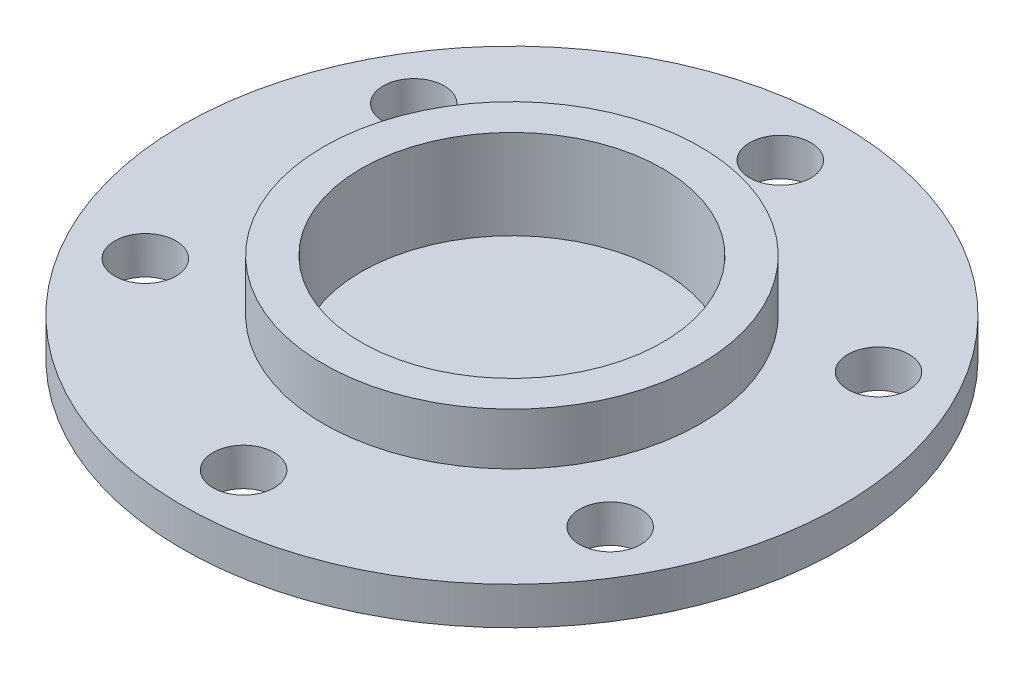
SolidWorks part; units mm, degrees
ref_plane "Front Plane" through (0, 0, 0) normal (0, 0, 1) x (1, 0, 0)
ref_plane "Top Plane" through (0, 0, 0) normal (0, 1, 0) x (1, 0, 0)
ref_plane "Right Plane" through (0, 0, 0) normal (1, 0, 0) x (0, 0, -1)
sketch "Sketch1" plane through (0, 0, 0) normal (0, 0, 1) x (1, 0, 0)
  line L0 (0, -4) -> (0, -14.5)
  line L1 (0, 0) -> (0, -26.9976) construction
  line L3 (-20.064, -4) -> (-35, -4)
  line L4 (-35, -4) -> (-35, 0)
  line L5 (-35, 0) -> (-20, 0)
  line L6 (-20, 0) -> (-20, 5.5)
  line L7 (-20, 5.5) -> (-16, 5.5)
  line L8 (-16, 5.5) -> (-16, -4)
  line L9 (-16, -4) -> (0, -4)
  line L10 (-20.064, -4) -> (0, -14.5)
  line L11 (-4.6488, -20.8543) -> (4.793, -20.8543) construction
  point P4 (0, -14.5)
  dimension "D1" = 9.5
  dimension "D2" = 20
  dimension "D4" = 5.5
  dimension "D6" = 4
  dimension "D8" = 4
revolve "Revolve1" add sketch "Sketch1" angle 360 about L1
sketch "Sketch2" plane through (0, -4, 0) normal (0, -1, 0) x (1, 0, 0)
  circle A0 centre (0, 0) radius 28.5 construction
  circle A1 centre (0, 28.5) radius 3.25
  circle A2 centre (24.6817, 14.25) radius 3.25
  circle A3 centre (24.6817, -14.25) radius 3.25
  circle A4 centre (0, -28.5) radius 3.25
  circle A5 centre (-24.6817, -14.25) radius 3.25
  circle A6 centre (-24.6817, 14.25) radius 3.25
  point P17 (0, 0)
  dimension "D1" = 57
  dimension "D2" = 6.5
  dimension "D3" = 6
extrude "Cut-Extrude1" cut sketch "Sketch2" against normal blind 10
